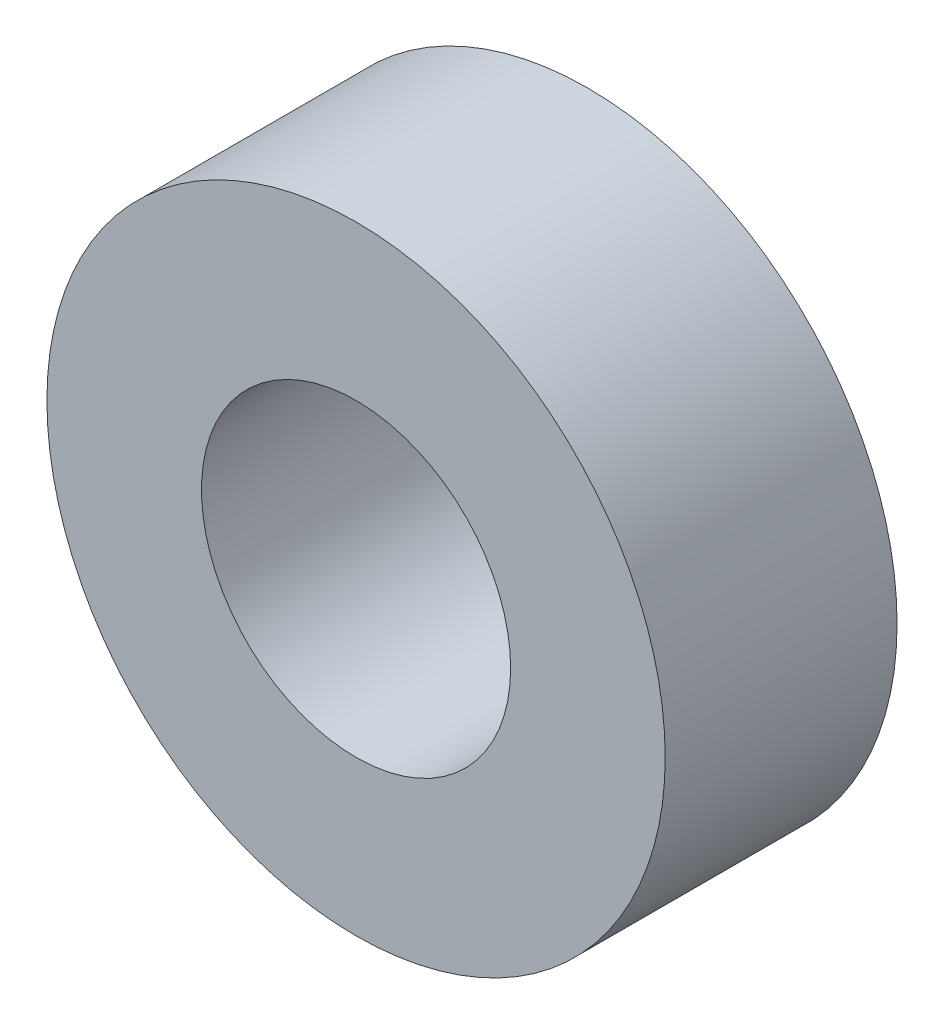
SolidWorks part; units mm, degrees
ref_plane "Piano frontale" through (0, 0, 0) normal (0, 0, 1) x (1, 0, 0)
ref_plane "Piano superiore" through (0, 0, 0) normal (0, 1, 0) x (1, 0, 0)
ref_plane "Piano destro" through (0, 0, 0) normal (1, 0, 0) x (0, 0, -1)
sketch "Schizzo1" plane through (0, 0, 0) normal (0, 0, 1) x (1, 0, 0)
  circle A0 centre (0, 0) radius 4
  circle A1 centre (0, 0) radius 2
  dimension "D1" = 8
  dimension "D2" = 4
extrude "Estrusione-Estrusione1" add sketch "Schizzo1" along normal blind 3
